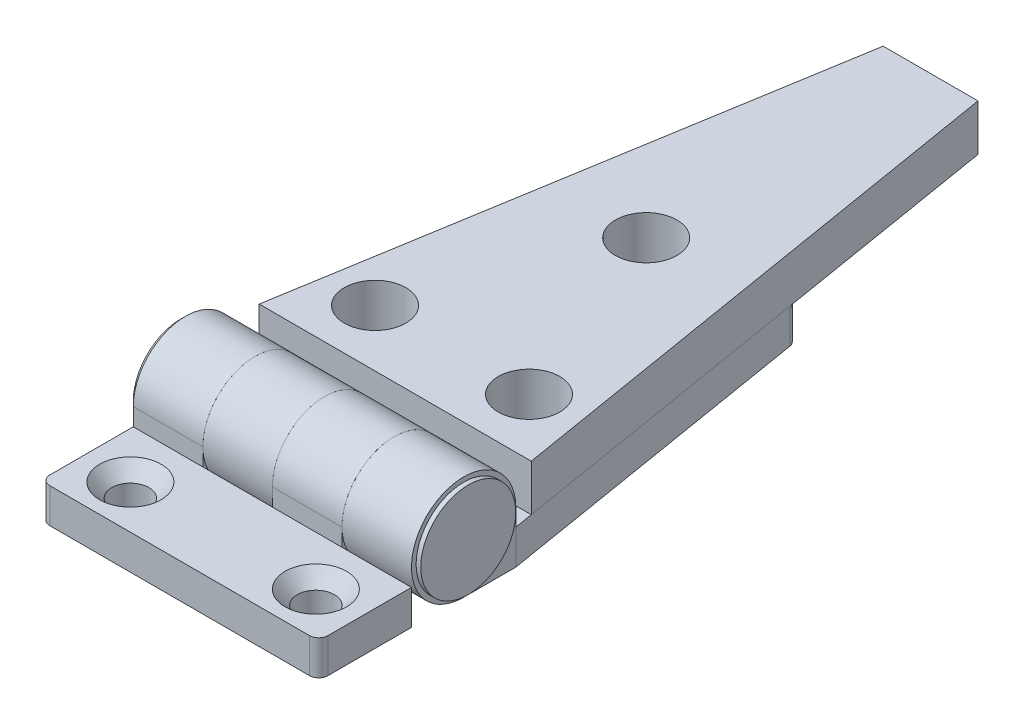
SolidWorks part; units mm, degrees
ref_plane "Front" through (0, 0, 0) normal (0, 0, 1) x (1, 0, 0)
ref_plane "Top" through (0, 0, 0) normal (0, 1, 0) x (1, 0, 0)
ref_plane "Right" through (0, 0, 0) normal (1, 0, 0) x (0, 0, -1)
sketch "Sketch1" plane through (0, 0, 0) normal (1, 0, 0) x (0, 0, -1)
  line L0 (-19.8438, -2.394) -> (-6.7307, -2.394) construction
  line L2 (-7.1437, 0) -> (-7.1438, -2.394)
  line L3 (0, -7.1437) -> (-19.8438, -7.1438)
  line L4 (-19.8438, -2.394) -> (-19.8438, -7.1438)
  line L5 (-19.8438, -2.394) -> (-7.1438, -2.394)
  line L6 (-19.8438, -7.1438) -> (53.1812, -7.1438) construction
  circle A0 centre (0, 0) radius 2.3813
  arc A2 (-6.7307, -2.394) -> (0, -7.1437) centre (0, 0) cw construction
  arc A3 (0, -7.1437) -> (-7.1437, 0) centre (0, 0) ccw
  dimension "D1" = 14.2875
  dimension "Pin Dia" = 4.7625
  dimension "D2" = 19.8438
  dimension "Th" = 4.7498
  dimension "Open Wd" = 73.025
extrude "Left Leaf" add sketch "Sketch1" along normal mid plane 38.1
sketch "Sketch2" plane through (0, 0, 0) normal (0, 1, 0) x (1, 0, 0)
  line L0 (19.05, -7.1437) -> (-19.05, -7.1437) construction
  line L3 (-19.05, 7.1437) -> (-9.525, 7.1437) construction
  line L4 (-19.05, 7.1437) -> (-19.05, -7.1437) construction
  line L5 (-19.05, -7.1437) -> (-9.525, -7.1437) construction
  line L6 (-19.05, 7.1437) -> (-19.05, -7.1437) construction
  line L7 (9.525, 7.1437) -> (19.05, 7.1437)
  line L8 (-9.525, 7.1437) -> (0, 7.1437)
  line L9 (-9.525, 7.1437) -> (-9.525, -7.1437)
  line L10 (-9.525, -7.1437) -> (0, -7.1437)
  line L11 (9.525, 7.1437) -> (9.525, -7.1437)
  line L12 (0, 7.1437) -> (9.525, 7.1437) construction
  line L13 (19.05, -7.1437) -> (19.05, 7.1437) construction
  line L14 (0, 7.1437) -> (0, -7.1437)
  line L15 (0, -7.1437) -> (9.525, -7.1437) construction
  line L16 (9.525, -7.1437) -> (19.05, -7.1437)
  line L17 (19.05, 7.1437) -> (19.05, -7.1437)
  line L18 (19.05, 7.1437) -> (-19.05, 7.1437) construction
extrude "Cut-Extrude1" cut sketch "Sketch2" against normal through all and the other way through all
sketch "Sketch3" plane through (0, 0, 0) normal (1, 0, 0) x (0, 0, -1)
  line L0 (0, 17.042) -> (0, -15.7543) construction
  line L1 (53.1812, -2.394) -> (53.1812, -7.1438)
  line L2 (-19.8438, -7.1438) -> (53.1812, -7.1438) construction
  line L3 (7.1438, 0) -> (7.1438, -2.394)
  line L4 (7.1438, -2.394) -> (53.1812, -2.394)
  line L6 (-19.8438, -2.394) -> (-19.8438, -7.1438) construction
  line L19 (0, -7.1438) -> (53.1812, -7.1438)
  circle A1 centre (0, 0) radius 2.3813 construction
  arc A4 (7.1438, 0) -> (0, -7.1438) centre (0, 0) ccw
  circle A5 centre (0, 0) radius 2.3813
extrude "Right Leaf" add sketch "Sketch3" along normal mid plane 38.1 separate body
sketch "Sketch9" plane through (0, 0, 0) normal (0, 1, 0) x (1, 0, 0)
  line L1 (0, 7.1437) -> (9.525, 7.1437)
  line L2 (0, 7.1437) -> (0, -7.1437)
  line L3 (0, -7.1437) -> (9.525, -7.1437)
  line L4 (9.525, 7.1437) -> (9.525, -7.1437)
  line L5 (-19.05, 7.1437) -> (-9.525, 7.1437)
  line L6 (-19.05, 7.1437) -> (-19.05, -7.1437)
  line L7 (-19.05, -7.1437) -> (-9.525, -7.1437)
  line L8 (-9.525, 7.1437) -> (-9.525, -7.1437)
extrude "Cut-Extrude2" cut sketch "Sketch9" against normal through all and the other way through all
sketch "Sketch10" plane through (0, 0, 0) normal (1, 0, 0) x (0, 0, -1)
  circle A0 centre (0, 0) radius 2.3813
  circle A1 centre (0, 0) radius 2.3813 construction
extrude "Extrude1" add sketch "Sketch10" along normal mid plane 38.1 separate body
sketch "Sketch13" plane through (0, -2.394, 0) normal (0, 1, 0) x (-1, 0, 0)
  line L0 (19.05, -7.1437) -> (11.43, -53.1812)
  line L3 (-19.05, -53.1812) -> (19.05, -53.1812) construction
  line L4 (-19.05, -7.1437) -> (-11.43, -53.1812)
  line L9 (11.43, -53.1812) -> (-11.43, -53.1812)
  line L10 (19.05, -7.1437) -> (19.05, -66.0771)
  line L11 (19.05, -66.0771) -> (-19.05, -66.0771)
  line L12 (-19.05, -66.0771) -> (-19.05, -7.1437)
  dimension "D1" = 22.86
  dimension "D2" = 12.8958
extrude "Cut-Extrude3" cut sketch "Sketch13" against normal through all
fillet "Fillet1" radius 1.27 2 edges at (-19.05, -4.7689, 19.8438) (19.05, -4.7689, 19.8438)
fillet "Fillet2" radius 1.27 2 edges at (11.43, -4.7689, -53.1812) (-11.43, -4.7689, -53.1812)
sketch "Sketch11" plane through (0, -2.394, 0) normal (0, 1, 0) x (-1, 0, 0)
  line L0 (-19.05, -7.1437) -> (-19.05, 7.1437) construction
  line L1 (-17.78, 19.8438) -> (17.78, 19.8438) construction
  line L2 (11.43, -53.1812) -> (-11.43, -53.1812) construction
  line L6 (0, 19.8438) -> (0, -53.1812) construction
  line L8 (19.05, 0) -> (-19.05, 0) construction
  line L9 (0, -53.1812) -> (0, 19.8438) construction
  point P6 (0, -44.0531)
  point P7 (10.541, -17.4625)
  point P10 (-10.541, -17.4625)
  point P12 (12.7, 13.8906)
  point P13 (-12.7, 13.8906)
  dimension "D1" = 13.8906
  dimension "D2" = 17.4625
  dimension "D3" = 21.082
  dimension "D4" = 26.5906
  dimension "D5" = 25.4
hole_wizard "CSK for #8 Flat Head Machine Screw1" positions "3DSketch1" profile "Sketch12" countersink size "#8" standard "Ansi Inch" end condition through all
sketch3d "3DSketch1"
  point P18 (0, -2.394, -44.0531)
  point P22 (-10.541, -2.394, -17.4625)
  point P25 (10.541, -2.394, -17.4625)
  point P28 (-12.7, -2.394, 13.8906)
  point P31 (12.7, -2.394, 13.8906)
sketch "Sketch12" plane through (0, -2.394, -44.0531) normal (1, 0, 0) x (0, 0, 1)
  line L0 (0, 0) -> (0, 4.7498)
  line L1 (0, 4.7498) -> (2.54, 4.7498)
  line L2 (2.54, 4.7498) -> (2.54, 1.9285)
  line L3 (2.54, 1.9285) -> (4.2164, 0)
  line L5 (4.2164, 0) -> (0, 0)
  line L6 (-2.54, 1.9285) -> (-4.2164, 0) construction
  line L11 (0, -6.35) -> (0, 107.95) construction
  dimension "Thru Hole Dia." = 5.08
  dimension "Thru Hole Depth" = 4.7498
  dimension "Near C'Sink Dia." = 8.4328
  dimension "Near C'Sink Angle" = 82
ref_plane "Plane1" through (0, 0, 0) normal (0, 1, 0) x (-1, 0, 0)
sketch "Sketch14" plane through (0, 0, 0) normal (0, 1, 0) x (-1, 0, 0)
  line L0 (-9.525, -7.1437) -> (-19.05, -7.1437) construction
  line L1 (-19.05, 0) -> (-19.685, 0)
  line L2 (-19.05, 0) -> (-19.05, -6.5088)
  line L3 (-19.05, -6.5088) -> (-19.685, -6.5088)
  line L5 (-19.685, 0) -> (-19.685, -6.5088)
  line L6 (19.05, 0) -> (19.685, 0)
  line L7 (19.05, 0) -> (19.05, -6.5087)
  line L8 (19.05, -6.5087) -> (19.685, -6.5087)
  line L9 (19.685, 0) -> (19.685, -6.5087)
  line L10 (19.05, 0) -> (-19.05, 0) construction
  dimension "D1" = 0.635
  dimension "D2" = 0.635
revolve "Revolve1" add sketch "Sketch14" angle 360 about L10
sketch "Sketch15" plane through (0, -2.394, 0) normal (0, 1, 0) x (1, 0, 0)
  line L4 (0.8583, 7.1437) -> (0.8583, 9.6837) construction
  line L5 (9.525, 7.1437) -> (0, 7.1437) construction
  line L6 (18.6296, 9.6837) -> (-18.6296, 9.6837)
  line L10 (11.6059, 52.1186) -> (19.05, 7.1437) construction
  line L11 (-19.05, 7.1437) -> (-11.6059, 52.1186) construction
  line L13 (18.6296, 9.6837) -> (10.6417, 57.9438)
  line L19 (-10.6417, 57.9438) -> (-6.494, 83.0028)
  line L20 (10.6417, 57.9438) -> (6.494, 83.0028)
  line L21 (-10.6417, 57.9438) -> (10.6417, 57.9438)
  line L22 (-10.6417, 57.9438) -> (-18.6296, 9.6837)
  line L23 (-6.494, 83.0028) -> (6.494, 83.0028)
  circle M5 centre (0, 44.0531) radius 4.2164
  circle M6 centre (-10.541, 17.4625) radius 4.2164
  circle M7 centre (10.541, 17.4625) radius 4.2164
  line M8 (19.05, 7.1437) -> (11.6059, 52.1186)
  arc M9 (11.6059, 52.1186) -> (10.3529, 53.1812) centre (10.3529, 51.9112) ccw
  line M10 (10.3529, 53.1812) -> (-10.3529, 53.1812)
  arc M11 (-10.3529, 53.1812) -> (-11.6059, 52.1186) centre (-10.3529, 51.9112) ccw
  line M12 (-11.6059, 52.1186) -> (-19.05, 7.1437)
extrude "Boss-Extrude5" add sketch "Sketch15" along normal blind 6.35 separate body contours L6 M8 M9 M10 M11 M12 M6 M7 M5 | L21 L22 L13 M11 M10 M9 | L23 L19 L21 L20
